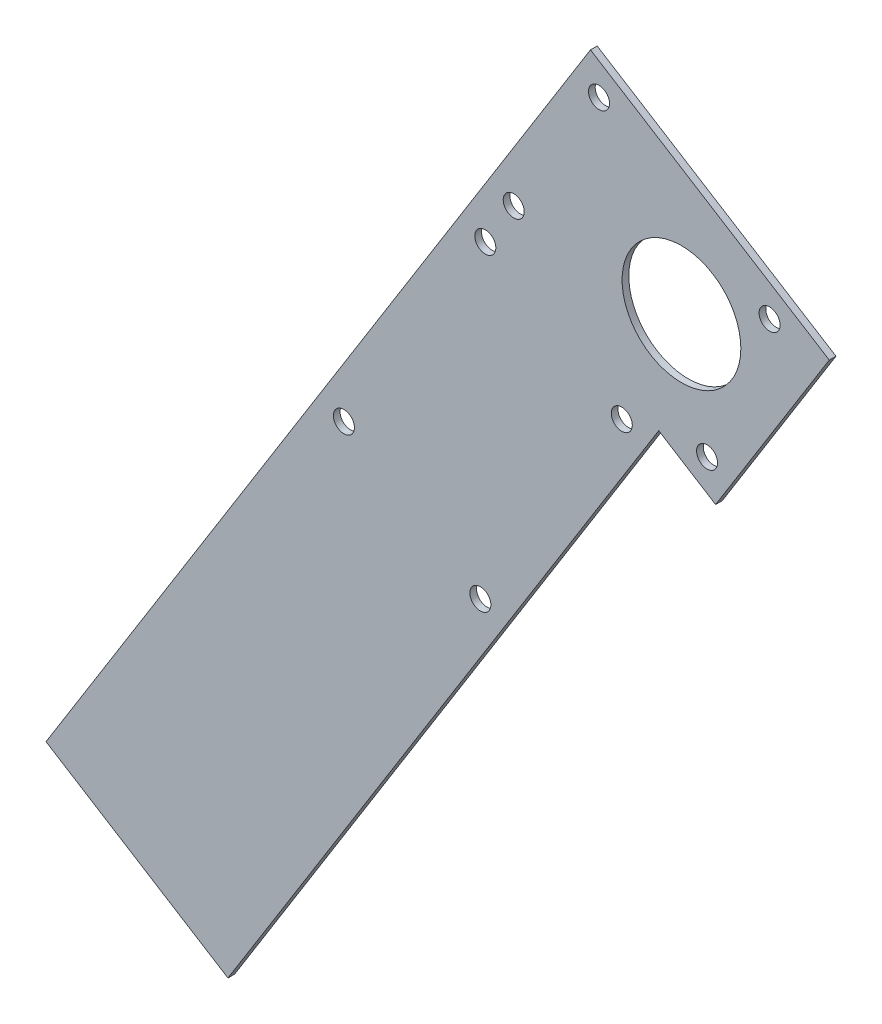
SolidWorks part; units mm, degrees
ref_plane "Front Plane" through (0, 0, 0) normal (0, 0, 1) x (1, 0, 0)
ref_plane "Top Plane" through (0, 0, 0) normal (0, 1, 0) x (1, 0, 0)
ref_plane "Right Plane" through (0, 0, 0) normal (1, 0, 0) x (0, 0, -1)
sketch "Sketch2" plane through (0, 0, 375.9739) normal (0, 0, -1) x (-1, 0, 0)
  line L1 (-54.5235, -26.5823) -> (-27.6036, -69.6631)
  line L2 (-27.6036, -69.6631) -> (-14.1408, -61.2506)
  line L3 (-14.1408, -61.2506) -> (87.8513, -224.4722)
  line L4 (-14.1408, -61.2506) -> (154.1085, -330.5059) construction
  line L5 (87.8513, -224.4722) -> (130.9322, -197.5523)
  line L6 (28.94, -34.3308) -> (197.1894, -303.586) construction
  line L7 (130.9322, -197.5523) -> (2.0201, 8.7501)
  line L8 (112.4148, 77.7323) -> (-54.5235, -26.5823) construction
  line L9 (2.0201, 8.7501) -> (-54.5235, -26.5823)
extrude "Boss-Extrude1" add sketch "Sketch2" along normal blind 1.5875
hole_wizard "#10 Clearance Hole1" positions "Sketch3" profile "Sketch4" hole size "#10" standard "ANSI Inch" end condition through all
sketch "Sketch3" plane through (0, 0, 374.3864) normal (0, 0, -1) x (-1, 0, 0)
  point P0 (-5.3907, -63.2708)
  point P3 (-25.5835, -60.913)
  point P6 (-40.3883, -25.2374)
  point P9 (0, 0)
  point P12 (20.1899, -32.3106)
  point P15 (26.9199, -43.0808)
  point P18 (60.4039, -96.6664)
  point P21 (28.0932, -116.8563)
sketch "Sketch4" plane through (5.3907, -63.2708, 374.3864) normal (1, 0, 0) x (0, 1, 0)
  line L0 (0, 0) -> (0, 1.5875)
  line L1 (0, 1.5875) -> (2.4892, 1.5875)
  line L2 (2.4892, 1.5875) -> (2.4892, 0)
  line L5 (2.4892, 0) -> (0, 0)
  line L11 (0, -6.35) -> (0, 107.95) construction
  dimension "Thru Hole Dia." = 4.9784
  dimension "Thru Hole Depth" = 1.5875
sketch "Sketch5" plane through (0, 0, 375.9739) normal (0, 0, 1) x (1, 0, 0)
  circle A0 centre (19.5231, -34.6627) radius 14.0572
extrude "Cut-Extrude1" cut sketch "Sketch5" against normal blind 2.54
